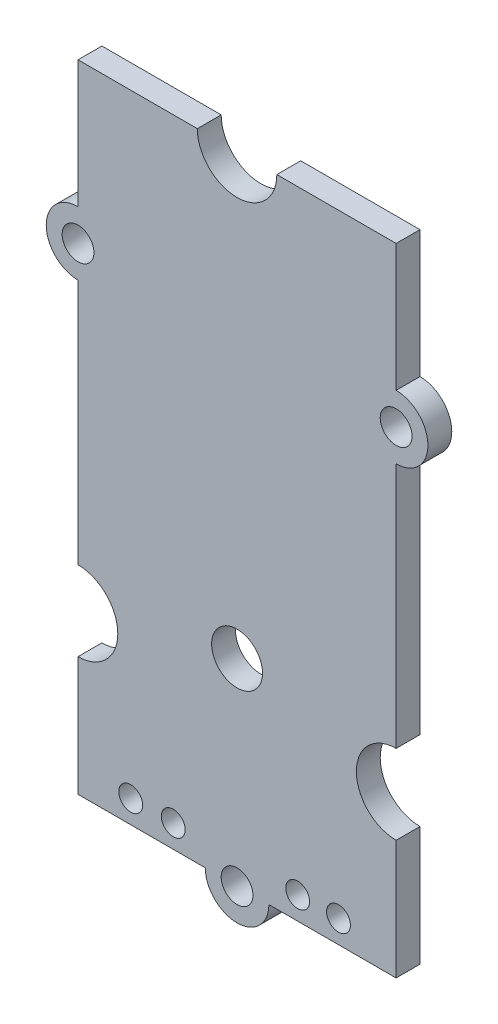
SolidWorks part; units mm, degrees
ref_plane "Plan de face" through (0, 0, 0) normal (0, 0, 1) x (1, 0, 0)
ref_plane "Plan de dessus" through (0, 0, 0) normal (0, 1, 0) x (1, 0, 0)
ref_plane "Plan de droite" through (0, 0, 0) normal (1, 0, 0) x (0, 0, -1)
sketch "Esquisse2" plane through (0, 0, 0) normal (0, 0, 1) x (1, 0, 0)
  line L0 (0, 0) -> (0, 40) construction
  line L1 (-10, 0) -> (-2, 0)
  line L2 (-10, 40) -> (-10, 32)
  line L3 (-10, 40) -> (-2.5, 40)
  line L4 (-13.2878, 30) -> (19.8637, 30) construction
  line L5 (-13.2878, 10) -> (19.8637, 10) construction
  line L6 (-10, 0) -> (-10, 40) construction
  line L7 (-10, 0) -> (-10, 7.5)
  line L8 (-10, 12.5) -> (-10, 28)
  line L9 (10, 0) -> (10, 40) construction
  line L10 (10, 12.5) -> (10, 28)
  line L11 (10, 0) -> (10, 7.5)
  line L12 (10, 40) -> (2.5, 40)
  line L13 (10, 40) -> (10, 32)
  line L14 (10, 0) -> (2, 0)
  arc A0 (-2, 0) -> (2, 0) centre (0, 0) ccw
  arc A1 (-10, 32) -> (-10, 28) centre (-10, 30) ccw
  arc A2 (-10, 12.5) -> (-10, 7.5) centre (-10, 10) cw
  arc A3 (-2.5, 40) -> (2.5, 40) centre (0, 40) ccw
  arc A4 (10, 12.5) -> (10, 7.5) centre (10, 10) ccw
  arc A5 (10, 32) -> (10, 28) centre (10, 30) cw
  dimension "D5" = 20
  dimension "D6" = 2
  dimension "D7" = 2.5
  dimension "D8" = 2.5
  dimension "D1" = 10
  dimension "D2" = 8
  dimension "D3" = 10
  dimension "D4" = 7.5
extrude "PCB" add sketch "Esquisse2" along normal blind 1.5
sketch "Esquisse3" plane through (0, 0, 1.5) normal (0, 0, 1) x (1, 0, 0)
  line L0 (-10, 40) -> (-10, 0) construction
  line L1 (-10, 30) -> (0, 30) construction
  line L2 (0, 30) -> (0, 40) construction
  line L3 (0, 40) -> (0, -2) construction
  line L4 (8.8467, 1.4351) -> (-9.6225, 1.4351) construction
  arc A0 (-2, 0) -> (2, 0) centre (0, 0) ccw construction
  circle A1 centre (-10, 30) radius 1
  circle A2 centre (6.3774, 1.4351) radius 0.75
  circle A3 centre (10, 30) radius 1
  circle A4 centre (0, 0) radius 1
  circle A5 centre (3.8095, 1.4351) radius 0.75
  circle A6 centre (-4.0125, 1.4351) radius 0.75
  circle A7 centre (-6.689, 1.4351) radius 0.75
  dimension "D1" = 2
  dimension "D2" = 2
  dimension "D3" = 1.5
  dimension "D4" = 1.5
  dimension "D5" = 1.5
  dimension "D6" = 1.5
extrude "Trous" cut sketch "Esquisse3" against normal through all
hole_wizard "M3 Clearance Hole2" positions "Sketch4" profile "Sketch3" hole size "M3" standard "AS"
sketch "Sketch4" plane through (0, 0, 0) normal (0, 0, -1) x (-1, 0, 0)
  line L0 (0, 0) -> (0, 12.3952) construction
  point P2 (0, 12.3952)
sketch "Sketch3" plane through (0, 12.3952, 0) normal (1, 0, 0) x (0, 1, 0)
  line L0 (0, 0) -> (0, 5.9614)
  line L1 (0, 5.9614) -> (1.6, 5)
  line L2 (1.6, 5) -> (1.6, 0)
  line L5 (1.6, 0) -> (0, 0)
  line L10 (0, 5.9614) -> (-1.6, 5) construction
  line L11 (0, -6.35) -> (0, 107.95) construction
  dimension "Hole Dia." = 3.2
  dimension "Hole Depth" = 5
  dimension "Drill Angle" = 118
